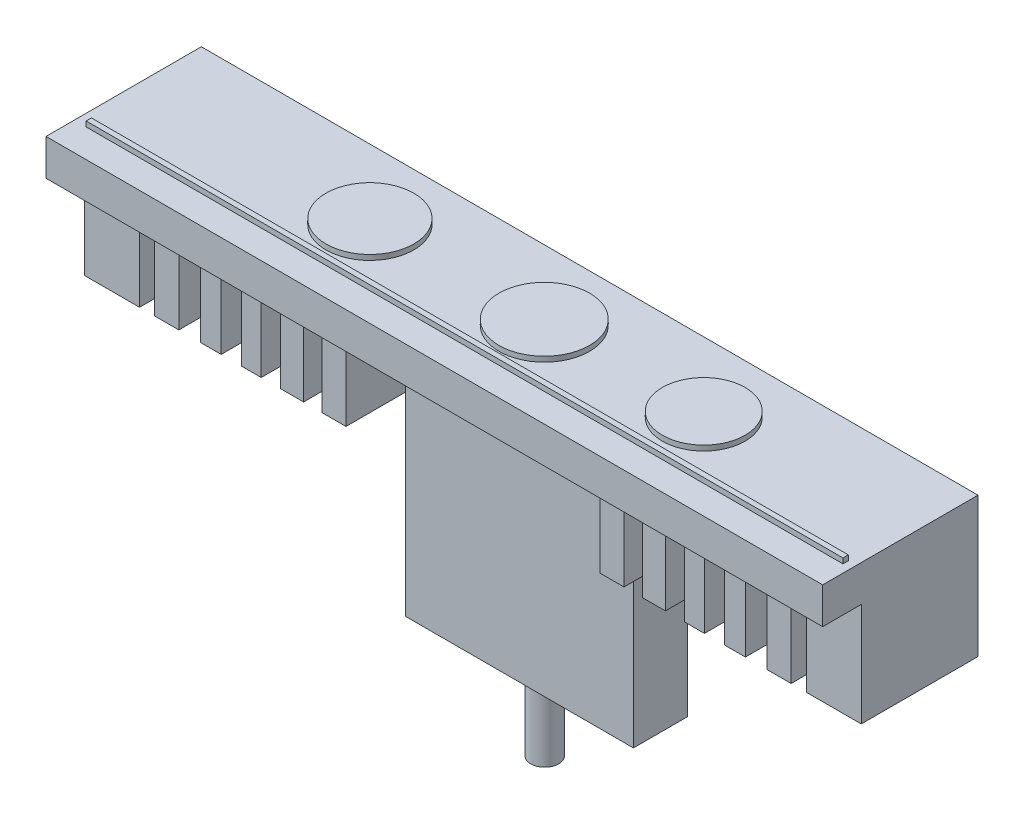
SolidWorks part; units mm, degrees
ref_plane "Front" through (0, 0, 0) normal (0, 0, 1) x (1, 0, 0)
ref_plane "Top" through (0, 0, 0) normal (0, 1, 0) x (1, 0, 0)
ref_plane "Right" through (0, 0, 0) normal (1, 0, 0) x (0, 0, -1)
sketch "Sketch1" plane through (0, 0, 0) normal (0, 1, 0) x (1, 0, 0)
  line L1 (0, 0) -> (150, 0)
  line L2 (0, 0) -> (0, 30)
  line L3 (0, 30) -> (150, 30)
  line L4 (150, 0) -> (150, 30)
  dimension "D1" = 150
  dimension "D2" = 30
extrude "Boss-Extrude1" add sketch "Sketch1" along normal blind 7
sketch "Sketch2" plane through (0, 7, 0) normal (0, 1, 0) x (1, 0, 0)
  line L1 (2.2837, 6.4862) -> (148.4607, 6.4862)
  line L2 (2.2837, 6.4862) -> (2.2837, 5.4627)
  line L3 (2.2837, 5.4627) -> (148.4607, 5.4627)
  line L4 (148.4607, 6.4862) -> (148.4607, 5.4627)
  circle A0 centre (46.0158, 16.5353) radius 8.4923
  circle A1 centre (79.6989, 16.5353) radius 8.7464
  circle A2 centre (110.4975, 16.5353) radius 7.9934
extrude "Boss-Extrude2" add sketch "Sketch2" along normal blind 1
sketch "Sketch3" plane through (0, 0, 0) normal (0, -1, 0) x (1, 0, 0)
  line L0 (150, -30) -> (0, -30) construction
  line L1 (150, -30) -> (139.3854, -30)
  line L2 (150, -30) -> (150, -7.4549)
  line L3 (150, -7.4549) -> (139.3854, -7.4549)
  line L4 (139.3854, -30) -> (139.3854, -7.4549)
  line L5 (136.4576, -30) -> (131.8053, -30)
  line L6 (136.4576, -30) -> (136.4576, -7.4549)
  line L7 (136.4576, -7.4549) -> (131.8053, -7.4549)
  line L8 (131.8053, -30) -> (131.8053, -7.4549)
  line L9 (150, -30) -> (0, -30) construction
  line L10 (127.6181, -30) -> (123.6171, -30)
  line L11 (127.6181, -30) -> (127.6181, -7.4549)
  line L12 (127.6181, -7.4549) -> (123.6171, -7.4549)
  line L13 (123.6171, -30) -> (123.6171, -7.4549)
  line L14 (75, 0) -> (75, -30) construction
  line L15 (119.7091, -30) -> (115.8942, -30)
  line L16 (119.7091, -30) -> (119.7091, -7.4549)
  line L17 (119.7091, -7.4549) -> (115.8942, -7.4549)
  line L18 (115.8942, -30) -> (115.8942, -7.4549)
  line L19 (112.1723, -30) -> (107.7061, -30)
  line L20 (112.1723, -30) -> (112.1723, -7.4549)
  line L21 (112.1723, -7.4549) -> (107.7061, -7.4549)
  line L22 (107.7061, -30) -> (107.7061, -7.4549)
  line L23 (104.1703, -30) -> (99.5179, -30)
  line L24 (104.1703, -30) -> (104.1703, -7.4549)
  line L25 (104.1703, -7.4549) -> (99.5179, -7.4549)
  line L26 (99.5179, -30) -> (99.5179, -7.4549)
  line L27 (0, 0) -> (150, 0) construction
  line L28 (50.4821, -30) -> (50.4821, -7.4549)
  line L29 (45.8297, -7.4549) -> (50.4821, -7.4549)
  line L30 (45.8297, -30) -> (45.8297, -7.4549)
  line L31 (45.8297, -30) -> (50.4821, -30)
  line L32 (42.2939, -30) -> (42.2939, -7.4549)
  line L33 (37.8277, -7.4549) -> (42.2939, -7.4549)
  line L34 (37.8277, -30) -> (37.8277, -7.4549)
  line L35 (37.8277, -30) -> (42.2939, -30)
  line L36 (34.1058, -30) -> (34.1058, -7.4549)
  line L37 (30.2909, -7.4549) -> (34.1058, -7.4549)
  line L38 (30.2909, -30) -> (30.2909, -7.4549)
  line L39 (30.2909, -30) -> (34.1058, -30)
  line L40 (26.3829, -30) -> (26.3829, -7.4549)
  line L41 (22.3819, -7.4549) -> (26.3829, -7.4549)
  line L42 (22.3819, -30) -> (22.3819, -7.4549)
  line L43 (22.3819, -30) -> (26.3829, -30)
  line L44 (18.1947, -30) -> (18.1947, -7.4549)
  line L45 (13.5424, -7.4549) -> (18.1947, -7.4549)
  line L46 (13.5424, -30) -> (13.5424, -7.4549)
  line L47 (13.5424, -30) -> (18.1947, -30)
  line L48 (10.6146, -30) -> (10.6146, -7.4549)
  line L49 (0, -7.4549) -> (10.6146, -7.4549)
  line L50 (0, -30) -> (0, -7.4549)
  line L51 (0, -30) -> (10.6146, -30)
extrude "Boss-Extrude3" add sketch "Sketch3" along normal blind 20
sketch "Sketch4" plane through (0, 0, 0) normal (0, -1, 0) x (1, 0, 0)
  line L0 (75, -16.4422) -> (75, 0) construction
  line L1 (97.0056, -26.912) -> (52.9944, -26.912)
  line L2 (97.0056, -26.912) -> (97.0056, -16.4422)
  line L3 (97.0056, -16.4422) -> (52.9944, -16.4422)
  line L4 (52.9944, -26.912) -> (52.9944, -16.4422)
  line L5 (0, 0) -> (150, 0) construction
extrude "Boss-Extrude4" add sketch "Sketch4" along normal blind 55
sketch "Sketch5" plane through (0, -55, 0) normal (0, -1, 0) x (1, 0, 0)
  circle A0 centre (74.7674, -21.5598) radius 2.6984
extrude "Boss-Extrude5" add sketch "Sketch5" along normal blind 15
